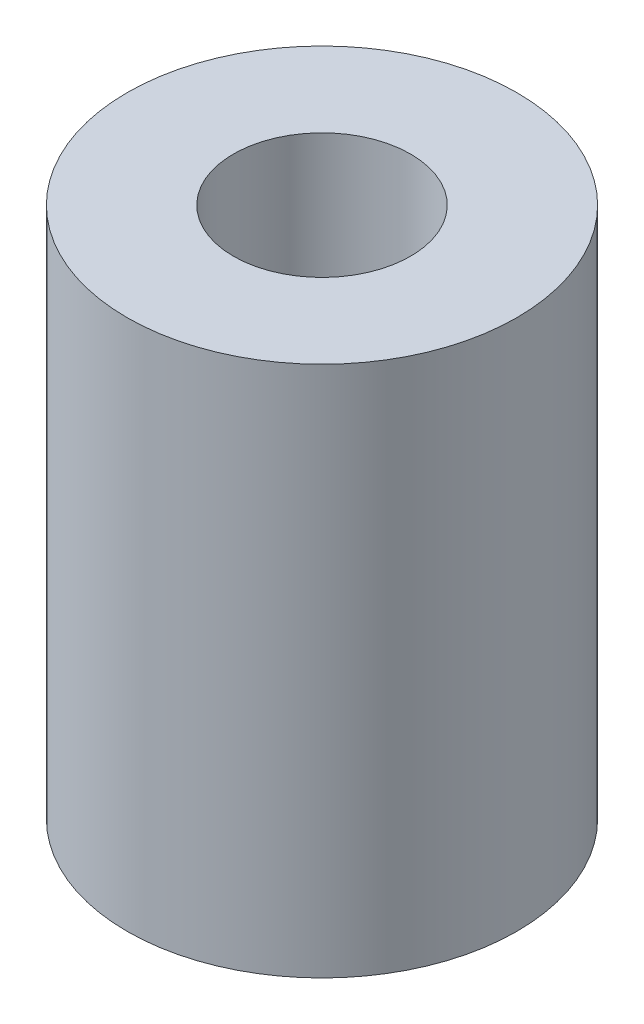
SolidWorks part; units mm, degrees
ref_plane "정면" through (0, 0, 0) normal (0, 0, 1) x (1, 0, 0)
ref_plane "윗면" through (0, 0, 0) normal (0, 1, 0) x (1, 0, 0)
ref_plane "우측면" through (0, 0, 0) normal (1, 0, 0) x (0, 0, -1)
sketch "스케치2" plane through (0, 0, 0) normal (0, 1, 0) x (1, 0, 0)
  circle A0 centre (0, 0) radius 11
  dimension "D1" = 22
extrude "보스-돌출1" add sketch "스케치2" along normal mid plane 30
sketch "스케치3" plane through (0, -15, 0) normal (0, -1, 0) x (1, 0, 0)
  circle A0 centre (0, 0) radius 2.5
  dimension "D1" = 5
extrude "컷-돌출1" cut sketch "스케치3" against normal through all
sketch "스케치4" plane through (0, 15, 0) normal (0, 1, 0) x (1, 0, 0)
  circle A0 centre (0, 0) radius 5
  dimension "D1" = 10
extrude "컷-돌출2" cut sketch "스케치4" against normal blind 20
